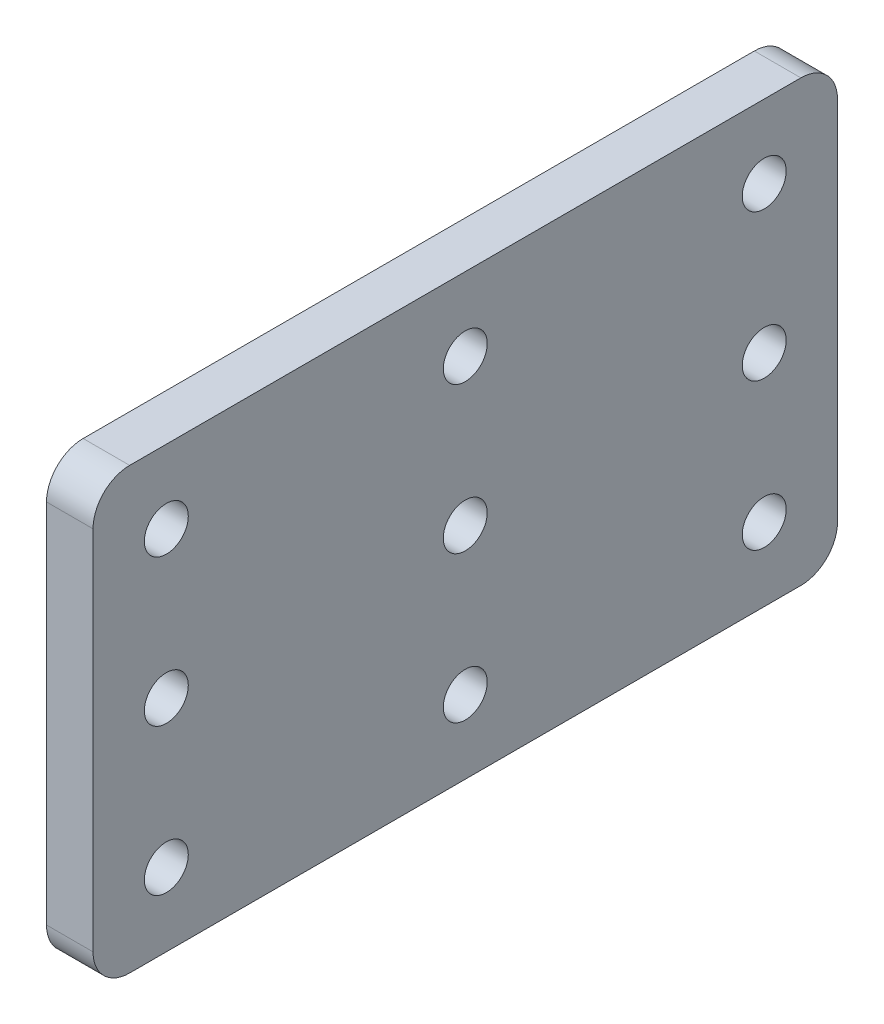
SolidWorks part; units mm, degrees
ref_plane "Front Plane" through (0, 0, 0) normal (0, 0, 1) x (1, 0, 0)
ref_plane "Top Plane" through (0, 0, 0) normal (0, 1, 0) x (1, 0, 0)
ref_plane "Right Plane" through (0, 0, 0) normal (1, 0, 0) x (0, 0, -1)
sketch "Sketch1" plane through (0, 0, 0) normal (0, 0, 1) x (1, 0, 0)
  line L0 (80.0083, 28.3887) -> (80.0083, -27.6113) construction
  line L1 (80.0083, 30) -> (86.3583, 30)
  line L2 (80.0083, 30) -> (80.0083, -30)
  line L3 (80.0083, -30) -> (86.3583, -30)
  line L4 (86.3583, 30) -> (86.3583, -30)
  line L5 (50.0083, 0) -> (80.0083, 0) construction
  line L7 (50.0083, -2.5) -> (50.0083, 2.5) construction
  line L12 (102.7119, 37.132) -> (102.7119, -22.863) construction
  line L13 (96.0083, 7.1345) -> (96.0083, 27.1345) construction
  dimension "D1" = 6.35
  dimension "D2" = 59.995
  dimension "D3" = 60
  dimension "D4" = 20
extrude "Boss-Extrude1" add sketch "Sketch1" along normal blind 101.6
sketch "Sketch2" plane through (86.3583, 0, 0) normal (1, 0, 0) x (0, 0, -1)
  line L0 (-10, 30) -> (-10, 20) construction
  line L1 (-101.6, 30) -> (0, 30) construction
  line L2 (-10, 20) -> (-10, 0) construction
  line L3 (-10, 0) -> (-10, -20) construction
  line L4 (-10, -20) -> (-10, -30) construction
  line L5 (-101.6, -30) -> (0, -30) construction
  line L6 (0, -30) -> (0, 30) construction
  line L7 (-50.8, 30) -> (-50.8, 20) construction
  line L8 (-50.8, 20) -> (-50.8, 0) construction
  line L9 (-50.8, 0) -> (-50.8, -20) construction
  line L10 (-50.8, -20) -> (-50.8, -30) construction
  circle A0 centre (-10, -20) radius 3
  circle A1 centre (-10, 20) radius 3
  circle A2 centre (-10, 0) radius 3
  circle A3 centre (-50.8, 20) radius 3
  circle A4 centre (-50.8, 0) radius 3
  circle A5 centre (-50.8, -20) radius 3
  circle A6 centre (-91.6, -20) radius 3
  circle A7 centre (-91.6, 0) radius 3
  circle A8 centre (-91.6, 20) radius 3
  dimension "D2" = 6
  dimension "D1" = 40
  dimension "D3" = 10
extrude "Cut-Extrude1" cut sketch "Sketch2" against normal blind 10
fillet "Fillet1" radius 5 4 edges at (83.1833, -30, 0) (83.1833, 30, 0) (83.1833, -30, 101.6) (83.1833, 30, 101.6)
